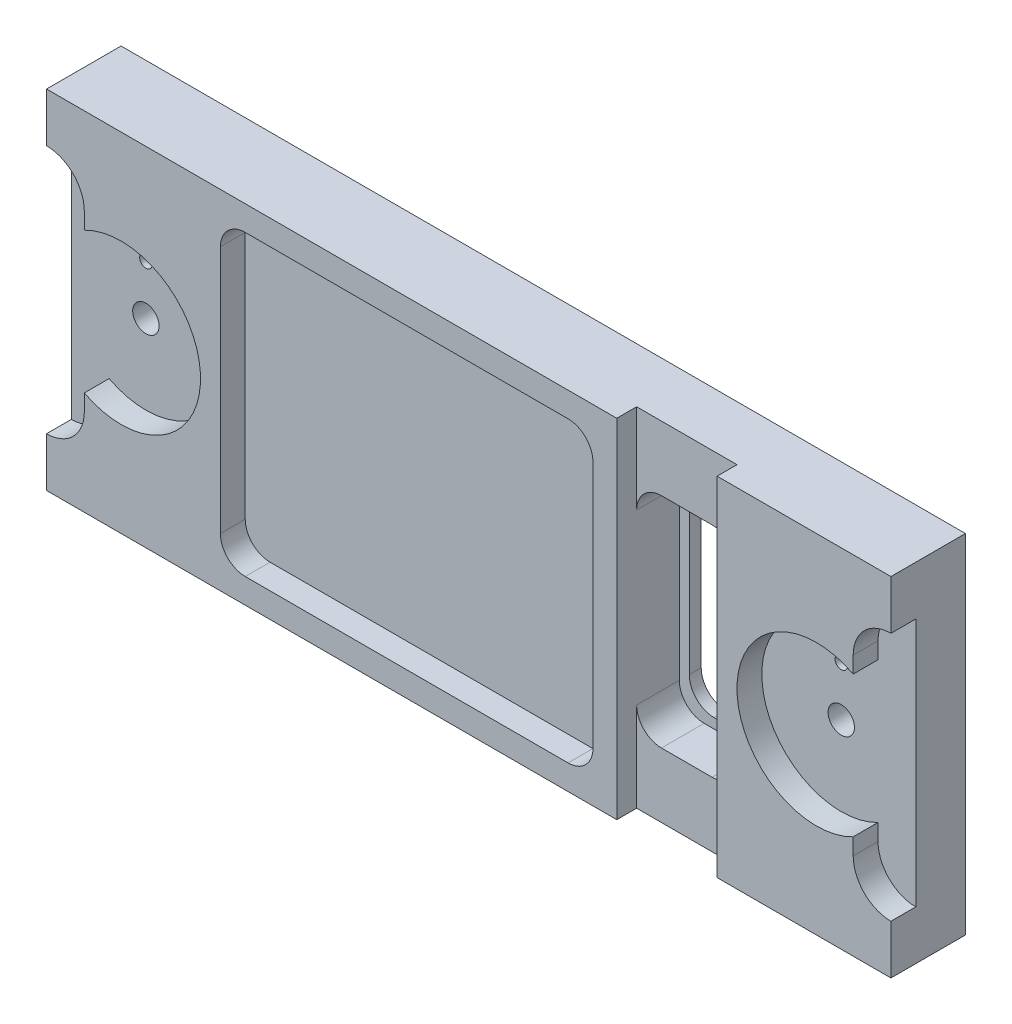
SolidWorks part; units mm, degrees
ref_plane "Front Plane" through (0, 0, 0) normal (0, 0, 1) x (1, 0, 0)
ref_plane "Top Plane" through (0, 0, 0) normal (0, 1, 0) x (1, 0, 0)
ref_plane "Right Plane" through (0, 0, 0) normal (1, 0, 0) x (0, 0, -1)
sketch "Sketch1" plane through (0, 0, 0) normal (0, 1, 0) x (1, 0, 0)
  line L1 (107.95, 9.525) -> (-107.95, 9.525)
  line L2 (107.95, 9.525) -> (107.95, -9.525)
  line L3 (107.95, -9.525) -> (-107.95, -9.525)
  line L4 (-107.95, 9.525) -> (-107.95, -9.525)
  line L5 (107.95, 9.525) -> (-107.95, -9.525) construction
  line L6 (107.95, -9.525) -> (-107.95, 9.525) construction
  point P0 (0, 0)
  dimension "D1" = 215.9
  dimension "D2" = 19.05
extrude "Boss-Extrude1" add sketch "Sketch1" along normal blind 88.9
sketch "Sketch2" plane through (0, 0, 9.525) normal (0, 0, 1) x (1, 0, 0)
  line L0 (-107.95, 88.9) -> (37.846, 88.9) construction
  line L1 (-107.95, 88.9) -> (107.95, 88.9) construction
  line L2 (-107.95, 0) -> (107.95, 0) construction
  line L3 (37.846, 88.9) -> (63.5, 88.9)
  line L4 (37.846, 88.9) -> (37.846, 0)
  line L5 (37.846, 0) -> (63.5, 0)
  line L6 (63.5, 88.9) -> (63.5, 0)
  dimension "D1" = 145.796
  dimension "D2" = 25.654
extrude "Cut-Extrude1" cut sketch "Sketch2" against normal blind 5.08
sketch "Sketch3" plane through (0, 0, 9.525) normal (0, 0, 1) x (1, 0, 0)
  line L0 (-107.95, 88.9) -> (-63.5, 88.9) construction
  line L1 (-107.95, 88.9) -> (37.846, 88.9) construction
  line L2 (-63.5, 88.9) -> (-63.5, 82.55) construction
  line L4 (-57.15, 82.55) -> (25.4, 82.55)
  line L5 (-63.5, 76.2) -> (-63.5, 12.7)
  line L6 (-57.15, 6.35) -> (25.4, 6.35)
  line L7 (31.75, 76.2) -> (31.75, 12.7)
  arc A0 (-63.5, 12.7) -> (-57.15, 6.35) centre (-57.15, 12.7) ccw
  arc A1 (25.4, 6.35) -> (31.75, 12.7) centre (25.4, 12.7) ccw
  arc A2 (-63.5, 76.2) -> (-57.15, 82.55) centre (-57.15, 76.2) cw
  arc A3 (25.4, 82.55) -> (31.75, 76.2) centre (25.4, 76.2) cw
  point P11 (-63.5, 6.35)
  point P19 (31.75, 82.55)
  dimension "D5" = 6.35
  dimension "D1" = 44.45
  dimension "D2" = 6.35
  dimension "D3" = 76.2
  dimension "D4" = 95.25
extrude "Cut-Extrude2" cut sketch "Sketch3" against normal blind 6.35
sketch "Sketch5" plane through (0, 0, 4.445) normal (0, 0, 1) x (1, 0, 0)
  line L0 (37.846, 88.9) -> (37.846, 0) construction
  line L1 (44.196, 72.39) -> (57.15, 72.39)
  line L2 (37.846, 66.04) -> (37.846, 22.86)
  line L3 (44.196, 16.51) -> (57.15, 16.51)
  line L4 (63.5, 66.04) -> (63.5, 22.86)
  line L5 (63.5, 0) -> (63.5, 88.9) construction
  arc A0 (57.15, 16.51) -> (63.5, 22.86) centre (57.15, 22.86) ccw
  arc A1 (37.846, 22.86) -> (44.196, 16.51) centre (44.196, 22.86) ccw
  arc A2 (44.196, 72.39) -> (37.846, 66.04) centre (44.196, 66.04) ccw
  arc A3 (57.15, 72.39) -> (63.5, 66.04) centre (57.15, 66.04) cw
  point P11 (63.5, 16.51)
  point P16 (37.846, 72.39)
  point P19 (63.5, 72.39)
  dimension "D3" = 6.35
  dimension "D1" = 55.88
  dimension "D2" = 16.51
sketch "Sketch6" plane through (0, 0, 4.445) normal (0, 0, 1) x (1, 0, 0)
  line L1 (46.736, 69.85) -> (54.61, 69.85)
  line L2 (40.386, 63.5) -> (40.386, 25.4)
  line L3 (46.736, 19.05) -> (54.61, 19.05)
  line L4 (60.96, 63.5) -> (60.96, 25.4)
  arc A0 (54.61, 19.05) -> (60.96, 25.4) centre (54.61, 25.4) ccw
  arc A1 (40.386, 25.4) -> (46.736, 19.05) centre (46.736, 25.4) ccw
  arc A2 (46.736, 69.85) -> (40.386, 63.5) centre (46.736, 63.5) ccw
  arc A3 (54.61, 69.85) -> (60.96, 63.5) centre (54.61, 63.5) cw
  point P7 (60.96, 19.05)
  point P10 (40.386, 19.05)
  point P13 (40.386, 69.85)
  point P16 (60.96, 69.85)
  dimension "D5" = 6.35
  dimension "D1" = 20.574
  dimension "D2" = 50.8
  dimension "D3" = 2.54
  dimension "D4" = 19.05
extrude "Cut-Extrude3" cut sketch "Sketch6" against normal through all
extrude "Cut-Extrude4" cut sketch "Sketch5" against normal blind 10.922
sketch "Sketch8" plane through (0, 0, 9.525) normal (0, 0, 1) x (1, 0, 0)
  line L0 (-107.95, 66.675) -> (-107.95, 22.225) construction
  line L1 (-107.95, 88.9) -> (-107.95, 0) construction
  line L2 (-98.298, 66.675) -> (-98.298, 22.225)
  line L3 (-117.602, 66.675) -> (-117.602, 22.225)
  arc A1 (-98.298, 66.675) -> (-117.602, 66.675) centre (-107.95, 66.675) ccw
  arc A2 (-117.602, 22.225) -> (-98.298, 22.225) centre (-107.95, 22.225) ccw
  arc A3 (-98.298, 26.4339) -> (-98.298, 62.4661) centre (-88.9, 44.45) ccw
  point P1 (-88.9, 44.45)
  point P2 (-107.95, 44.45)
  dimension "D1" = 20.32
  dimension "D4" = 9.652
  dimension "D2" = 44.45
  dimension "D3" = 19.05
  dimension "D5" = 44.45
  dimension "D6" = 22.225
extrude "Cut-Extrude5" cut sketch "Sketch8" against normal blind 6.35
sketch "Sketch9" plane through (0, 0, 9.525) normal (0, 0, 1) x (1, 0, 0)
  line L0 (-88.9, 57.15) -> (-88.9, 44.45) construction
  circle A1 centre (-88.9, 44.45) radius 3.3734
  circle A2 centre (-88.9, 57.15) radius 1.5875
  dimension "D2" = 6.7469
  dimension "D4" = 3.175
  dimension "D1" = 12.7
extrude "Cut-Extrude6" cut sketch "Sketch9" against normal through all
sketch "Sketch10" plane through (0, 0, -9.525) normal (0, 0, -1) x (-1, 0, 0)
  circle A0 centre (88.9, 44.45) radius 4.7625
  dimension "D1" = 9.525
extrude "Cut-Extrude7" cut sketch "Sketch10" against normal blind 6.35
mirror "Mirror1" about plane through (0, 0, 0) normal (1, 0, 0) of "Cut-Extrude5", "Cut-Extrude6", "Cut-Extrude7"
